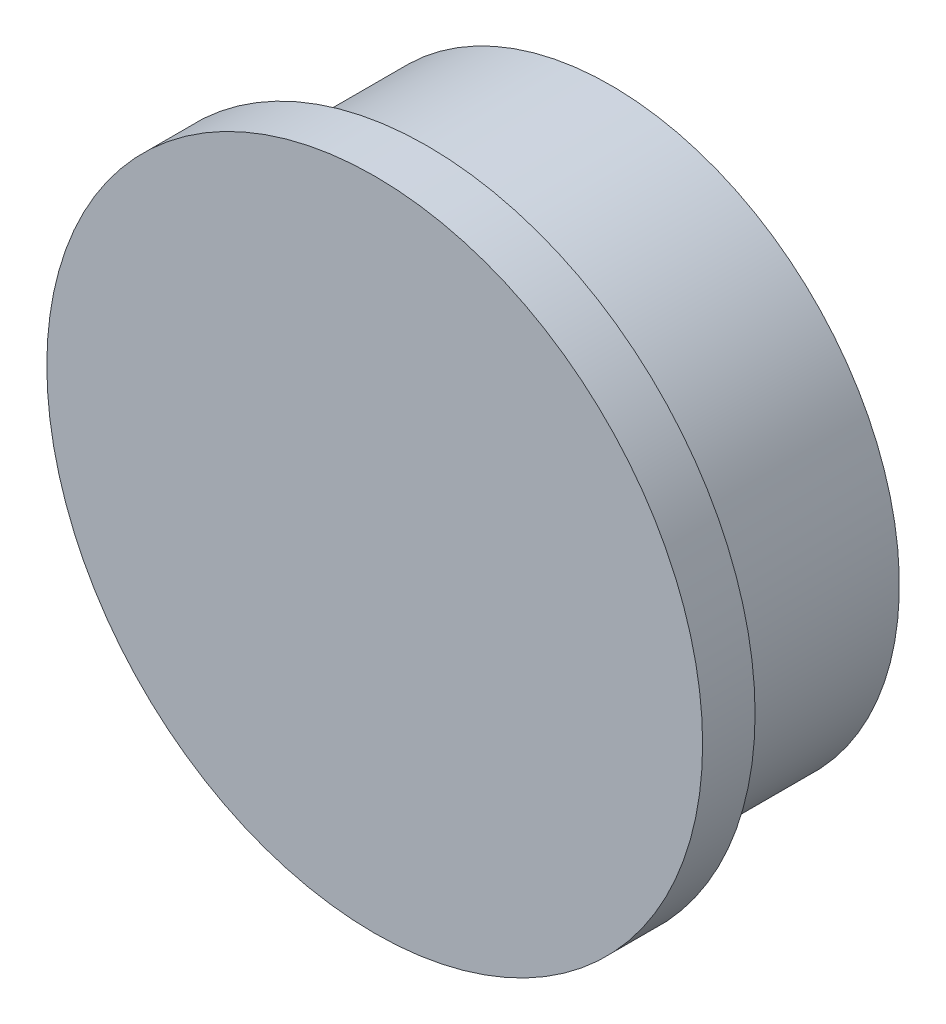
SolidWorks part; units mm, degrees
ref_plane "Alzado" through (0, 0, 0) normal (0, 0, 1) x (1, 0, 0)
ref_plane "Planta" through (0, 0, 0) normal (0, 1, 0) x (1, 0, 0)
ref_plane "Vista lateral" through (0, 0, 0) normal (1, 0, 0) x (0, 0, -1)
sketch "Croquis1" plane through (0, 0, 0) normal (0, 0, 1) x (1, 0, 0)
  circle A0 centre (0, 0) radius 12.5
  dimension "D1" = 25
extrude "Saliente-Extruir1" add sketch "Croquis1" along normal blind 2
sketch "Croquis2" plane through (0, 0, 0) normal (0, 0, -1) x (-1, 0, 0)
  circle A0 centre (0, 0) radius 11
  dimension "D1" = 22
extrude "Saliente-Extruir2" add sketch "Croquis2" along normal blind 7 contours A0
